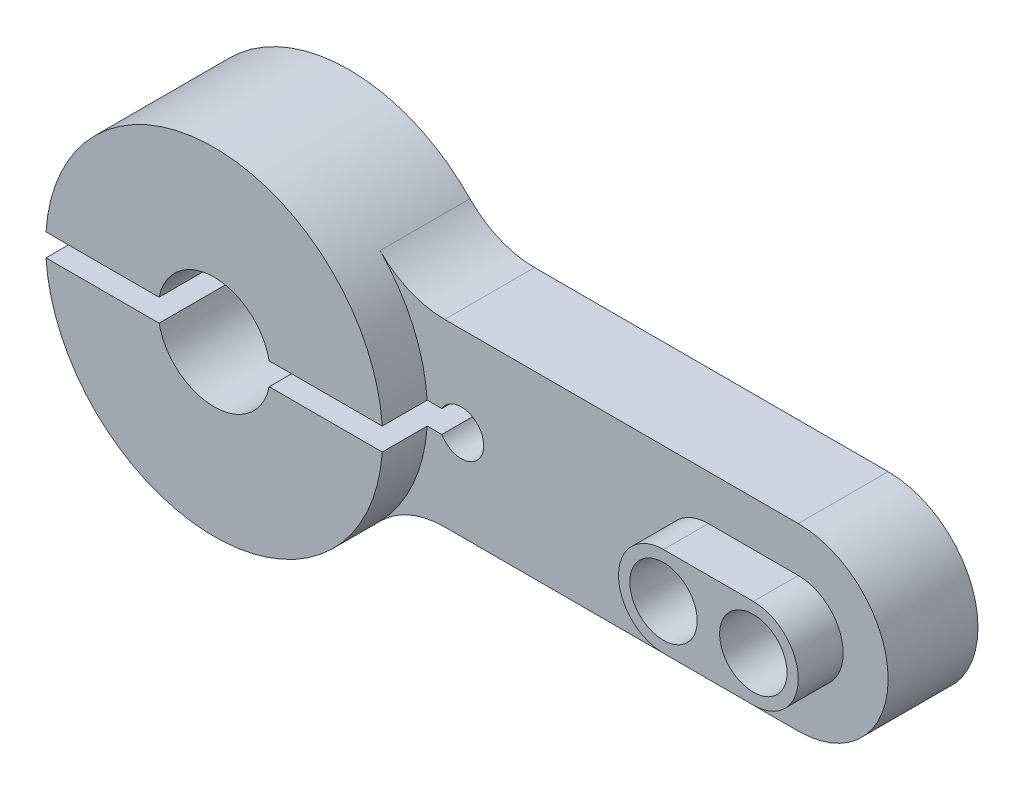
SolidWorks part; units mm, degrees
material "Plain Carbon Steel"
ref_plane "Front Plane" through (0, 0, 0) normal (0, 0, 1) x (1, 0, 0)
ref_plane "Top Plane" through (0, 0, 0) normal (0, 1, 0) x (1, 0, 0)
ref_plane "Right Plane" through (0, 0, 0) normal (1, 0, 0) x (0, 0, -1)
sketch "Sketch1" plane through (0, 0, 0) normal (0, 0, 1) x (1, 0, 0)
  line L0 (0, 0) -> (20, 0) construction
  line L1 (20, 0) -> (24, 0) construction
  line L2 (20, 0) -> (24, 0) construction
  line L3 (20, 2) -> (24, 2) construction
  line L4 (20, -2) -> (24, -2) construction
  line L5 (6.3443, 4) -> (24, 4)
  line L6 (6.3443, -4) -> (24, -4)
  arc A0 (6.3443, 4) -> (6.3443, -4) centre (0, 0) ccw
  circle A1 centre (20, 0) radius 1.5 construction
  circle A2 centre (24, 0) radius 1.5 construction
  arc A3 (20, 2) -> (20, -2) centre (20, 0) ccw construction
  arc A4 (24, -2) -> (24, 2) centre (24, 0) ccw construction
  arc A5 (24, 4) -> (24, -4) centre (24, 0) cw
  circle A6 centre (0, 0) radius 2.5 construction
  point P7 (22, 0)
  point P12 (22, 2)
  dimension "D1" = 15
  dimension "D4" = 3
  dimension "D5" = 3
  dimension "D9" = 4
  dimension "D10" = 5
  dimension "D2" = 20
  dimension "D3" = 4
  dimension "D6" = 4
  dimension "D7" = 4
  dimension "D8" = 4
extrude "Boss-Extrude1" add sketch "Sketch1" along normal blind 6
fillet "Fillet1" radius 4 2 edges at (6.3443, -4, 3) (6.3443, 4, 3)
sketch "Sketch2" plane through (0, 0, 6) normal (0, 0, 1) x (1, 0, 0)
  line L1 (8.2614, -4) -> (24, -4) construction
  line L2 (24, 4) -> (8.2614, 4) construction
  line L3 (8.2614, -4) -> (24, -4)
  line L4 (24, 4) -> (8.2614, 4)
  line L5 (20, 2) -> (24, 2) construction
  line L6 (20, 2) -> (24, 2)
  line L7 (20, -2) -> (24, -2) construction
  line L8 (20, -2) -> (24, -2)
  arc A0 (5.3878, -5.2174) -> (5.3878, 5.2174) centre (0, 0) ccw
  arc A2 (5.3878, 5.2174) -> (8.2614, 4) centre (8.2614, 8) ccw construction
  arc A3 (8.2614, -4) -> (5.3878, -5.2174) centre (8.2614, -8) ccw construction
  arc A4 (24, -4) -> (24, 4) centre (24, 0) ccw construction
  arc A5 (8.2614, -4) -> (5.3878, -5.2174) centre (8.2614, -8) ccw
  arc A6 (24, -4) -> (24, 4) centre (24, 0) ccw
  arc A7 (5.3878, 5.2174) -> (8.2614, 4) centre (8.2614, 8) ccw
  arc A8 (24, -2) -> (24, 2) centre (24, 0) ccw construction
  arc A9 (20, 2) -> (20, -2) centre (20, 0) ccw construction
  arc A10 (24, -2) -> (24, 2) centre (24, 0) ccw
  arc A11 (20, 2) -> (20, -2) centre (20, 0) ccw
extrude "Cut-Extrude1" cut sketch "Sketch2" against normal blind 2
sketch "Sketch3" plane through (0, 0, 6) normal (0, 0, 1) x (1, 0, 0)
  circle A0 centre (20, 0) radius 1.5
  circle A1 centre (24, 0) radius 1.5
  circle A2 centre (24, 0) radius 1.5 construction
  circle A3 centre (20, 0) radius 1.5 construction
  circle A4 centre (0, 0) radius 2.5
  circle A5 centre (0, 0) radius 2.5 construction
extrude "Cut-Extrude2" cut sketch "Sketch3" against normal through all
sketch "Sketch4" plane through (0, 0, 6) normal (0, 0, 1) x (1, 0, 0)
  line L0 (0, 0) -> (20, 0) construction
  line L1 (-8.0794, 0.5) -> (8.134, 0.5)
  line L2 (8.134, -0.5) -> (-8.0794, -0.5)
  line L3 (-8.0794, -0.5) -> (-8.0794, 0.5)
  line L4 (-8.0794, 0) -> (0, 0) construction
  arc A0 (8.134, -0.5) -> (8.134, 0.5) centre (9, 0) ccw
  dimension "D1" = 2
  dimension "D2" = 9
  dimension "D3" = 0.5
  dimension "D4" = 0.5
  dimension "D5" = 8.0794
extrude "Cut-Extrude3" cut sketch "Sketch4" against normal through all
ref_plane "Plane1" through (0, 0, 0.762) normal (0, 0, -1) x (-1, 0, 0)
sketch "Sketch5" plane through (0, 0, 0.762) normal (0, 0, -1) x (-1, 0, 0)
  line L0 (-2.4495, 0.5) -> (-0.6568, 0.5)
  line L1 (-8.134, 0.5) -> (-2.4495, 0.5) construction
  line L2 (-2.4495, -0.5) -> (-0.6568, -0.5)
  line L3 (0.6568, 0.5) -> (2.4495, 0.5)
  line L4 (0.6568, -0.5) -> (2.4495, -0.5)
  arc A0 (-2.4495, 0.5) -> (2.4495, 0.5) centre (0, 0) cw
  arc A1 (-2.4495, -0.5) -> (2.4495, -0.5) centre (0, 0) ccw
  arc A2 (-2.4495, -0.5) -> (2.4495, -0.5) centre (0, 0) ccw construction
  arc A3 (2.4495, 0.5) -> (-2.4495, 0.5) centre (0, 0) ccw construction
  arc A4 (-0.6568, -0.5) -> (0.6568, -0.5) centre (0, 0) ccw
  arc A5 (0.6568, 0.5) -> (-0.6568, 0.5) centre (0, 0) ccw
  dimension "D1" = 1.651
extrude "Boss-Extrude2" add sketch "Sketch5" against normal blind 1.27
sketch "Sketch6" plane through (0, 0, 0) normal (0, 0, -1) x (-1, 0, 0)
  line L6 (7.4833, -0.5) -> (2.4495, -0.5)
  line L7 (-2.4495, -0.5) -> (-8.134, -0.5)
  line L8 (-8.134, 0.5) -> (-2.4495, 0.5)
  line L9 (2.4495, 0.5) -> (7.4833, 0.5)
  line L10 (-8.2614, 4) -> (-24, 4)
  line L11 (-24, -4) -> (-8.2614, -4)
  line L12 (7.4833, -0.5) -> (2.4495, -0.5)
  line L13 (-2.4495, -0.5) -> (-8.134, -0.5)
  line L14 (-8.134, 0.5) -> (-2.4495, 0.5)
  line L15 (2.4495, 0.5) -> (7.4833, 0.5)
  line L16 (-8.2614, 4) -> (-24, 4)
  line L17 (-24, -4) -> (-8.2614, -4)
  arc A8 (-5.3878, -5.2174) -> (7.4833, -0.5) centre (0, 0) ccw
  arc A9 (-2.4495, -0.5) -> (2.4495, -0.5) centre (0, 0) ccw
  arc A10 (-8.134, 0.5) -> (-8.134, -0.5) centre (-9, 0) ccw
  arc A11 (2.4495, 0.5) -> (-2.4495, 0.5) centre (0, 0) ccw
  arc A12 (7.4833, 0.5) -> (-5.3878, 5.2174) centre (0, 0) ccw
  arc A13 (-8.2614, 4) -> (-5.3878, 5.2174) centre (-8.2614, 8) ccw
  arc A14 (-24, 4) -> (-24, -4) centre (-24, 0) ccw
  arc A15 (-5.3878, -5.2174) -> (-8.2614, -4) centre (-8.2614, -8) ccw
  arc A16 (-5.3878, -5.2174) -> (7.4833, -0.5) centre (0, 0) ccw
  arc A17 (-2.4495, -0.5) -> (2.4495, -0.5) centre (0, 0) ccw
  arc A18 (-8.134, 0.5) -> (-8.134, -0.5) centre (-9, 0) ccw
  arc A19 (2.4495, 0.5) -> (-2.4495, 0.5) centre (0, 0) ccw
  arc A20 (7.4833, 0.5) -> (-5.3878, 5.2174) centre (0, 0) ccw
  arc A21 (-8.2614, 4) -> (-5.3878, 5.2174) centre (-8.2614, 8) ccw
  arc A22 (-24, 4) -> (-24, -4) centre (-24, 0) ccw
  arc A23 (-5.3878, -5.2174) -> (-8.2614, -4) centre (-8.2614, -8) ccw
  dimension "D1" = 0
